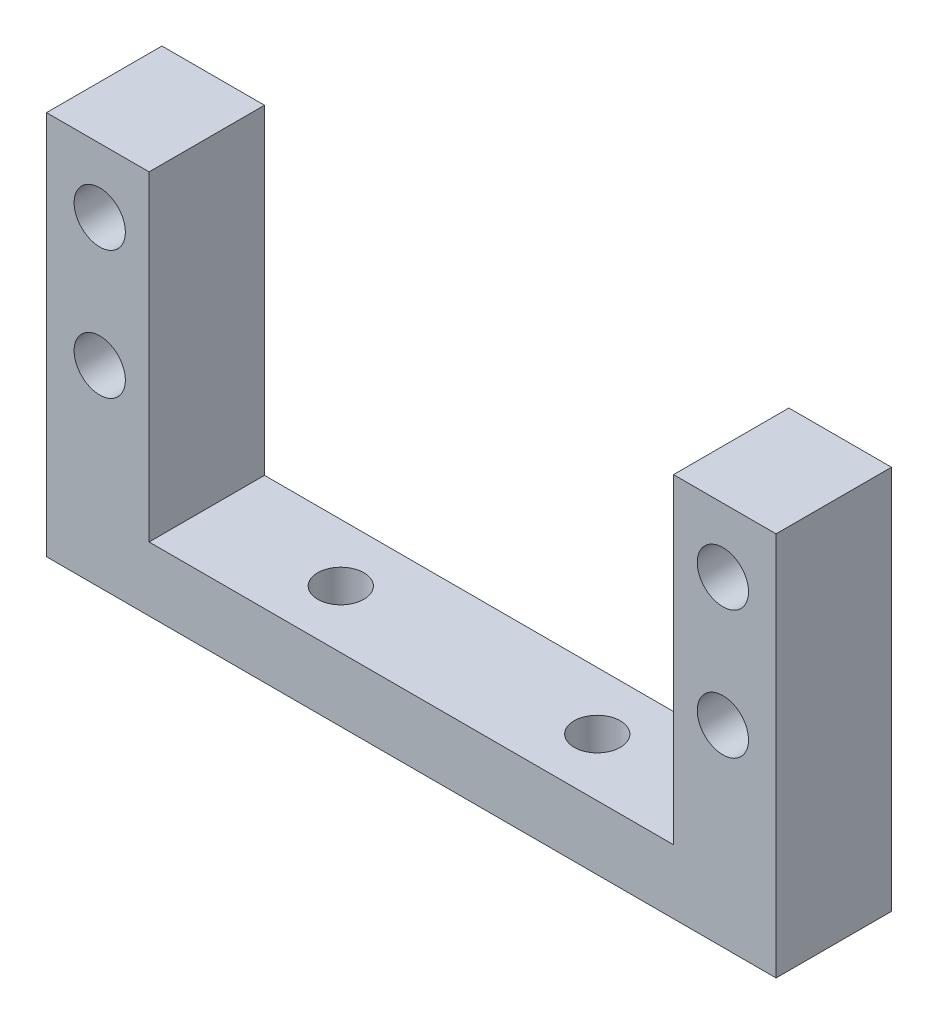
SolidWorks part; units mm, degrees
ref_plane "Plan de face" through (0, 0, 0) normal (0, 0, 1) x (1, 0, 0)
ref_plane "Plan de dessus" through (0, 0, 0) normal (0, 1, 0) x (1, 0, 0)
ref_plane "Plan de droite" through (0, 0, 0) normal (1, 0, 0) x (0, 0, -1)
sketch "Esquisse1" plane through (0, 0, 0) normal (0, 0, 1) x (1, 0, 0)
  line L0 (0, 0) -> (0, 30)
  line L1 (0, 0) -> (8, 0)
  line L2 (0, 30) -> (8, 30)
  line L3 (8, 0) -> (8, 30)
  line L5 (8, 0) -> (48.9, 0)
  line L6 (8, 5) -> (48.9, 5)
  line L8 (48.9, 0) -> (56.9, 0)
  line L9 (48.9, 0) -> (48.9, 30)
  line L10 (56.9, 0) -> (56.9, 30)
  line L11 (48.9, 30) -> (56.9, 30)
  line L12 (4.15, 30) -> (4.15, 0) construction
  line L14 (52.75, 0) -> (52.75, 30) construction
  circle A0 centre (4.15, 25) radius 2
  circle A1 centre (4.15, 15) radius 2
  circle A2 centre (52.75, 25) radius 2
  circle A3 centre (52.75, 15) radius 2
  dimension "D6" = 4
  dimension "D7" = 4
  dimension "D8" = 4
  dimension "D9" = 4
  dimension "D1" = 40.9
  dimension "D2" = 8
  dimension "D3" = 8
  dimension "D4" = 25
  dimension "D5" = 5
  dimension "D10" = 10
  dimension "D11" = 10
  dimension "D12" = 3.85
  dimension "D13" = 5
  dimension "D14" = 3.85
  dimension "D15" = 5
extrude "Boss.-Extru.1" add sketch "Esquisse1" along normal blind 9
sketch "Esquisse2" plane through (0, 0, 0) normal (0, -1, 0) x (1, 0, 0)
  line L0 (0, 4.5) -> (56.9, 4.5) construction
  line L1 (0, 9) -> (0, 0) construction
  line L2 (56.9, 9) -> (56.9, 0) construction
  circle A0 centre (18.45, 4.5) radius 1.8
  circle A1 centre (38.45, 4.5) radius 1.8
  point P12 (28.45, 4.5)
  dimension "D1" = 3.6
  dimension "D2" = 3.6
  dimension "D3" = 10
  dimension "D4" = 20
extrude "Enlèv. mat.-Extru.1" cut sketch "Esquisse2" against normal blind 9
